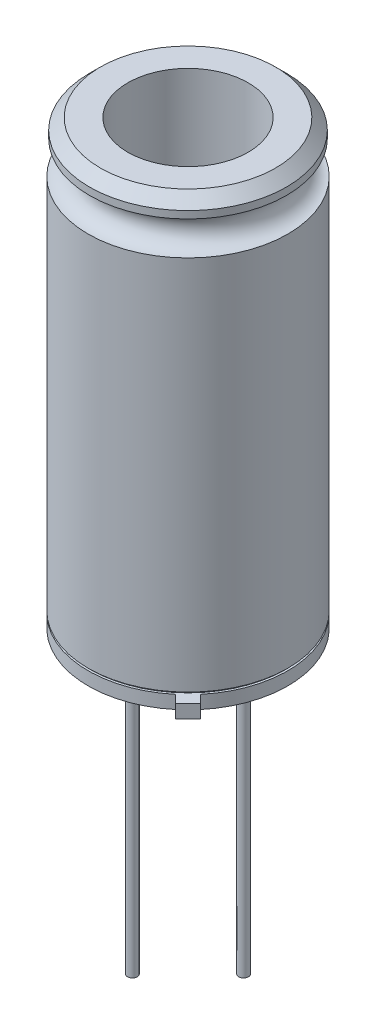
SolidWorks part; units mm, degrees
ref_plane "Piano frontale" through (0, 0, 0) normal (0, 0, 1) x (1, 0, 0)
ref_plane "Piano superiore" through (0, 0, 0) normal (0, 1, 0) x (1, 0, 0)
ref_plane "Piano destro" through (0, 0, 0) normal (1, 0, 0) x (0, 0, -1)
sketch "Schizzo1" plane through (0, 0, 0) normal (0, 1, 0) x (1, 0, 0)
  circle A0 centre (0, 0) radius 4.56
  dimension "D1" = 9.12
extrude "Estrusione-Estrusione1" add sketch "Schizzo1" along normal blind 19.5
sketch "Schizzo2" plane through (0, 0, 0) normal (0, 0, 1) x (1, 0, 0)
  line L0 (-4.56, 19.5) -> (-4.56, 0) construction
  line L1 (4.56, 19.5) -> (-4.56, 19.5) construction
  line L2 (0, 19.5) -> (0, 15.6496) construction
  circle A0 centre (-4.56, 17.92) radius 0.75
  dimension "D1" = 1.5
  dimension "D2" = 1.58
revolve "Taglia-Rivoluzione1" cut sketch "Schizzo2" angle 360 about L2
sketch "Schizzo3" plane through (0, 0, 0) normal (0, 0, 1) x (1, 0, 0)
  line L0 (0, 19.5) -> (0, 17.17) construction
  line L1 (-6.8929, 18.2289) -> (-4.5, 18.2289)
  line L2 (-6.8929, 18.2289) -> (-6.8929, 19.7375)
  line L3 (-6.8929, 19.7375) -> (-4.5, 19.7375)
  line L4 (-4.5, 18.2289) -> (-4.5, 19.7375)
  line L5 (-6.8929, 18.2289) -> (-4.5, 19.7375) construction
  line L6 (-6.8929, 19.7375) -> (-4.5, 18.2289) construction
  line L7 (4.56, 19.5) -> (-4.56, 19.5) construction
  line L8 (-4.56, 17.17) -> (4.56, 17.17) construction
  point P0 (-5.6964, 18.9832)
  dimension "D1" = 4.5
revolve "Taglia-Rivoluzione2" cut sketch "Schizzo3" angle 360 about L0
chamfer "Smusso1" distance 0.5 angle 45 1 edges at (0, 19.5, 4.5)
sketch "Schizzo4" plane through (0, 19.5, 0) normal (0, 1, 0) x (1, 0, 0)
  line L0 (0, 0) -> (4, 0)
  circle A0 centre (0, 0) radius 4 construction
hole_wizard "Foro per Vite M5-1" positions "Schizzo3D1" profile "Schizzo5" hole size "M5" standard "ISO" end condition up to next
sketch3d "Schizzo3D1"
  point P0 (0, 19.5, 0)
sketch "Schizzo5" plane through (0, 19.5, 0) normal (1, 0, 0) x (0, 0, 1)
  line L0 (0, 0) -> (0, 19.5)
  line L1 (0, 19.5) -> (2.75, 19.5)
  line L2 (2.75, 19.5) -> (2.75, 0)
  line L5 (2.75, 0) -> (0, 0)
  line L11 (0, -6.35) -> (0, 107.95) construction
  dimension "Thru Hole Dia." = 5.5
  dimension "Thru Hole Depth" = 19.5
cosmetic thread "Filettatura cosmetica1" parameters "D1"=5, "D2"=16.5
sketch "Schizzo7" plane through (0, 0, 0) normal (0, 0, 1) x (1, 0, 0)
  line L0 (0, 0) -> (0, -0.7)
  line L1 (0, -0.7) -> (-4.56, -0.7)
  line L2 (-4.56, -0.7) -> (-4.56, -0.1)
  line L3 (-4.56, -0.1) -> (-4.46, -0.1)
  line L4 (-4.46, -0.1) -> (-4.46, 0)
  line L5 (-4.56, 0) -> (4.56, 0) construction
  line L6 (-4.46, 0) -> (0, 0)
  line L7 (0, 19.5) -> (4, 19.5) construction
  line L8 (-4.56, 17.17) -> (-4.56, 0) construction
  dimension "D1" = 20.2
  dimension "D2" = 0.1
  dimension "D3" = 0.1
revolve "Rivoluzione1" add sketch "Schizzo7" angle 360 about L0
sketch "Schizzo8" plane through (0, -0.7, 0) normal (0, -1, 0) x (1, 0, 0)
  line L0 (0, 0) -> (3.578, 3.578) construction
  line L1 (0, 0) -> (4, 0) construction
  line L2 (0.2828, -0.2828) -> (3.8608, 3.2951)
  line L3 (-0.2828, 0.2828) -> (3.2951, 3.8608)
  line L4 (3.8608, 3.2951) -> (3.578, 3.578)
  line L5 (3.578, 3.578) -> (3.2951, 3.8608)
  line L6 (-0.2828, 0.2828) -> (0.2828, -0.2828)
  line L7 (3.2244, 3.2244) -> (4.0701, 2.3787) construction
  circle A0 centre (0, 0) radius 4.56 construction
  dimension "D1" = 45
  dimension "D4" = 0.5
  dimension "D2" = 0.4
  dimension "D3" = 0.4
extrude "Estrusione-Estrusione2" add sketch "Schizzo8" against normal up to surface (0.6 mm away) up to face at (-4.56, -0.1, 0)
sketch "Schizzo9" plane through (0, -0.7, 0) normal (0, -1, 0) x (1, 0, 0)
  circle A0 centre (0, 0) radius 2.54 construction
  circle A1 centre (0, 2.54) radius 0.8 construction
  circle A2 centre (2.54, 0) radius 0.8
  circle A3 centre (0, -2.54) radius 0.8
  circle A4 centre (-2.54, 0) radius 0.8
  dimension "D1" = 5.08
  dimension "D2" = 1.6
extrude "Taglio-Estrusione1" cut sketch "Schizzo9" against normal up to surface (0.6 mm away) up to face at (1.7859, -0.1, 1.7859)
sketch "Schizzo10" plane through (0, -0.1, 0) normal (0, -1, 0) x (1, 0, 0)
  circle A0 centre (0, 0) radius 2.54 construction
  circle A1 centre (0, 2.54) radius 0.225
  circle A2 centre (2.54, 0) radius 0.225
  circle A3 centre (0, -2.54) radius 0.225
  circle A4 centre (-2.54, 0) radius 0.225
  dimension "D1" = 0.45
extrude "Estrusione-Estrusione3" add sketch "Schizzo10" along normal blind 13
